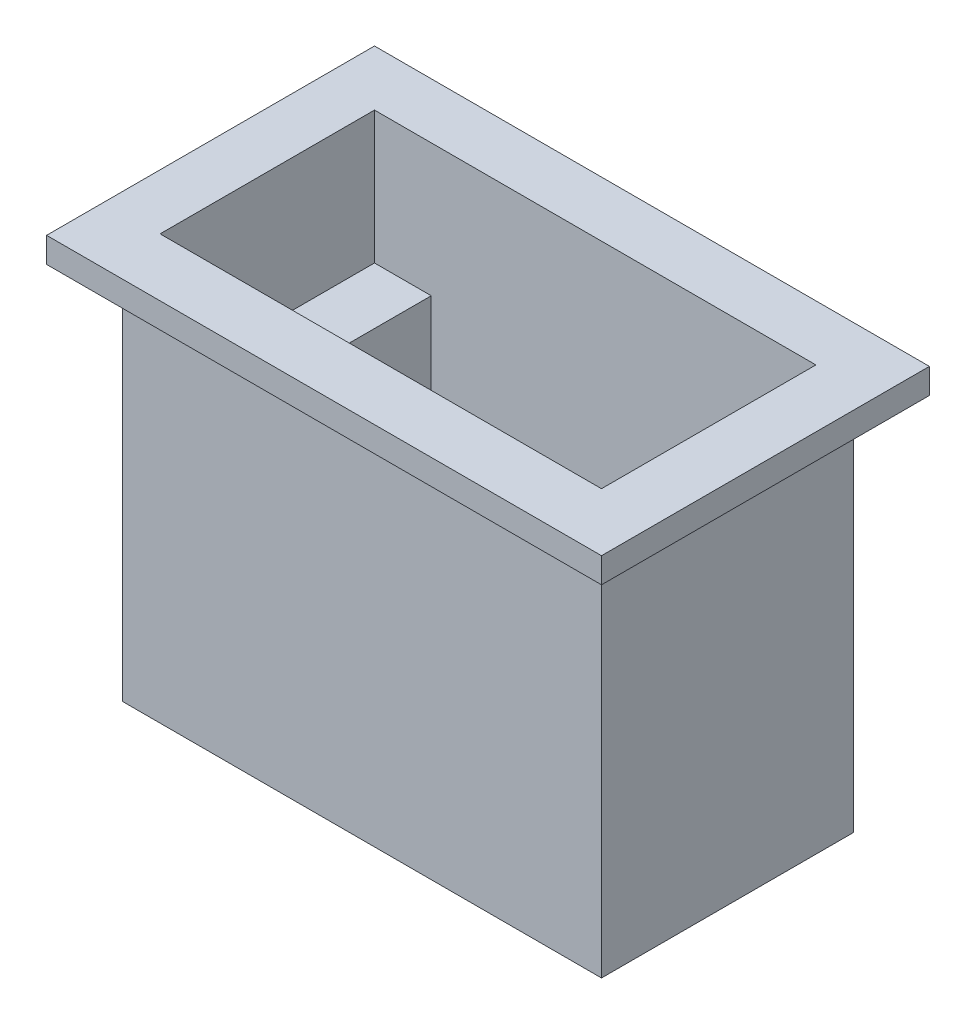
SolidWorks part; units mm, degrees
ref_plane "Front Plane" through (0, 0, 0) normal (0, 0, 1) x (1, 0, 0)
ref_plane "Top Plane" through (0, 0, 0) normal (0, 1, 0) x (1, 0, 0)
ref_plane "Right Plane" through (0, 0, 0) normal (1, 0, 0) x (0, 0, -1)
sketch "Sketch1" plane through (0, 0, 0) normal (0, 1, 0) x (1, 0, 0)
  line L1 (-10.4, 5.9429) -> (27.6, 5.9429)
  line L2 (-10.4, 5.9429) -> (-10.4, -14.0571)
  line L3 (-10.4, -14.0571) -> (27.6, -14.0571)
  line L4 (27.6, 5.9429) -> (27.6, -14.0571)
  dimension "D1" = 38
  dimension "D2" = 20
extrude "Boss-Extrude1" add sketch "Sketch1" along normal blind 32
sketch "Sketch2" plane through (0, 32, 0) normal (0, 1, 0) x (1, 0, 0)
  line L0 (27.6, 5.9429) -> (-10.4, 5.9429) construction
  line L1 (-9, 4.5429) -> (26, 4.5429)
  line L2 (-9, 4.5429) -> (-9, -12.4571)
  line L3 (-9, -12.4571) -> (26, -12.4571)
  line L4 (26, 4.5429) -> (26, -12.4571)
  line L5 (-10.4, 5.9429) -> (-10.4, -14.0571) construction
  dimension "D1" = 35
  dimension "D2" = 17
  dimension "D3" = 1.4
  dimension "D4" = 1.4
extrude "Cut-Extrude1" cut sketch "Sketch2" against normal blind 28
sketch "Sketch3" plane through (0, 4, 0) normal (0, 1, 0) x (1, 0, 0)
  line L0 (-9, -12.4571) -> (26, -12.4571) construction
  line L1 (-9, 4.5429) -> (-4.5, 4.5429)
  line L2 (-9, 4.5429) -> (-9, -12.4571)
  line L3 (-9, -12.4571) -> (-4.5, -12.4571)
  line L4 (-4.5, 4.5429) -> (-4.5, -12.4571)
  line L5 (26, 4.5429) -> (-9, 4.5429) construction
  line L6 (20, 4.5429) -> (26, 4.5429)
  line L7 (20, 4.5429) -> (20, -12.4571)
  line L8 (20, -12.4571) -> (26, -12.4571)
  line L9 (26, 4.5429) -> (26, -12.4571)
  dimension "D1" = 4.5
  dimension "D2" = 6
extrude "Boss-Extrude2" add sketch "Sketch3" along normal blind 17.5
sketch "Sketch4" plane through (0, 32, 0) normal (0, 1, 0) x (1, 0, 0)
  line L1 (-10.4, 5.9429) -> (27.6, 5.9429)
  line L2 (-10.4, 5.9429) -> (-10.4, -14.0571)
  line L3 (-10.4, -14.0571) -> (27.6, -14.0571)
  line L4 (27.6, 5.9429) -> (27.6, -14.0571)
extrude "Extrude-Thin2" add sketch "Sketch4" against normal blind 2 thin thin type one direction wall 3
